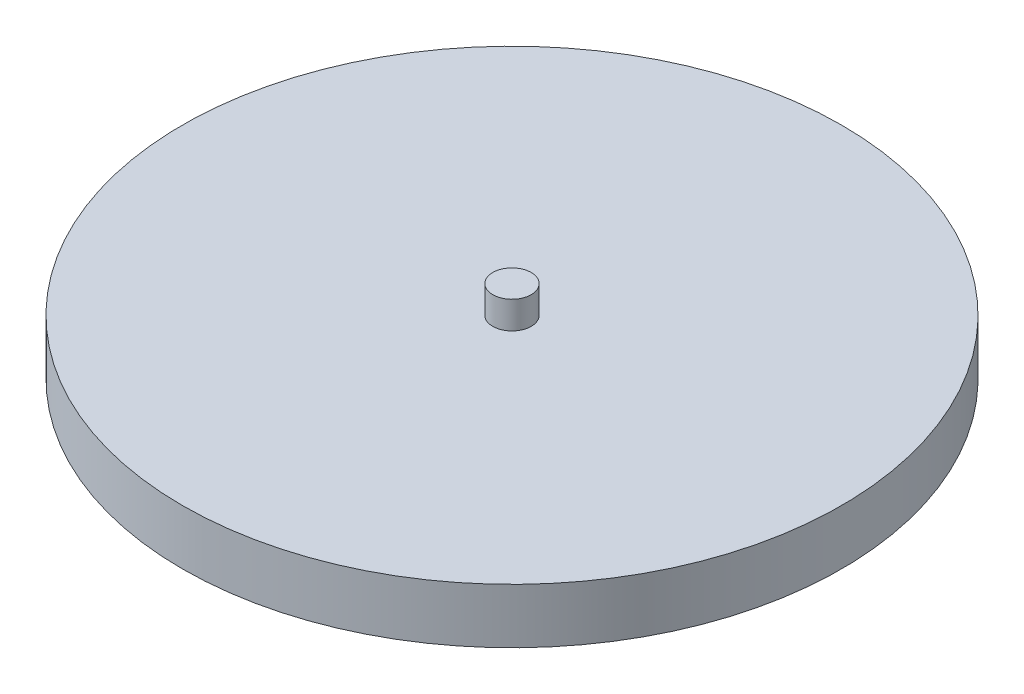
SolidWorks part; units mm, degrees
material "1060 Alloy"
ref_plane "Front Plane" through (0, 0, 0) normal (0, 0, 1) x (1, 0, 0)
ref_plane "Top Plane" through (0, 0, 0) normal (0, 1, 0) x (1, 0, 0)
ref_plane "Right Plane" through (0, 0, 0) normal (1, 0, 0) x (0, 0, -1)
sketch "Sketch1" plane through (0, 0, 0) normal (0, 1, 0) x (1, 0, 0)
  circle A0 centre (0, 0) radius 60
  dimension "D1" = 120
extrude "Boss-Extrude1" add sketch "Sketch1" along normal blind 10
sketch "Sketch2" plane through (0, 10, 0) normal (0, 1, 0) x (1, 0, 0)
  circle A0 centre (0, 0) radius 3.5
  dimension "D1" = 7
extrude "Boss-Extrude2" add sketch "Sketch2" along normal blind 5
